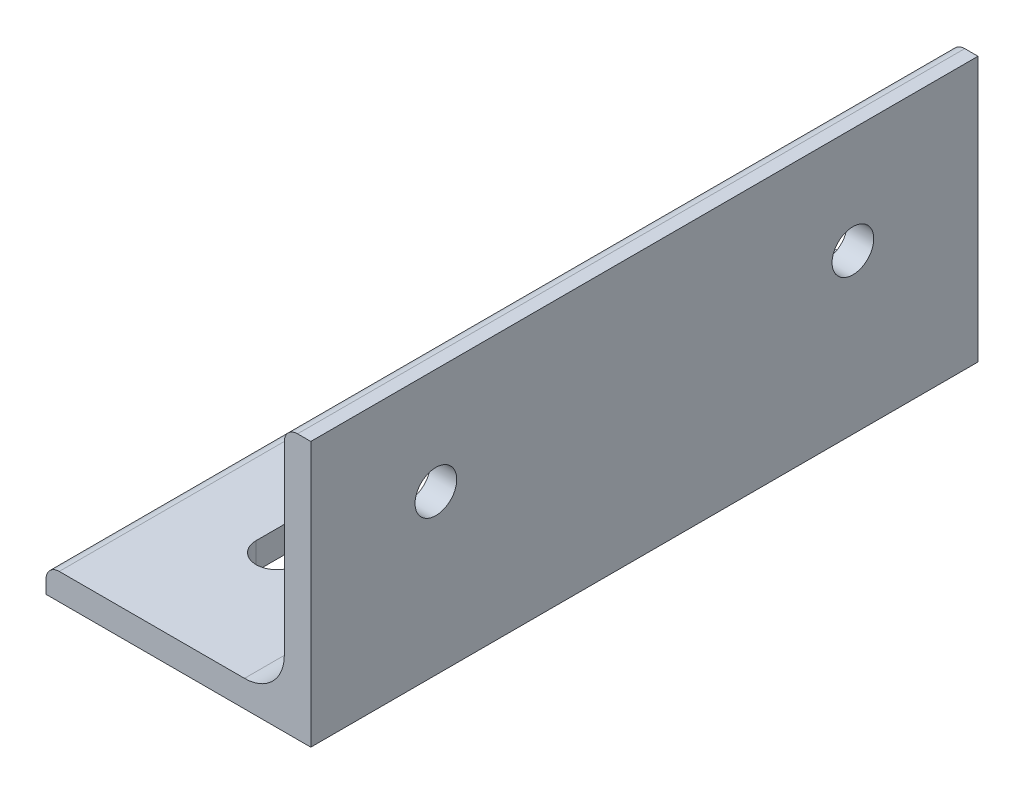
SolidWorks part; units mm, degrees
ref_plane "Front Plane" through (0, 0, 0) normal (0, 0, 1) x (1, 0, 0)
ref_plane "Top Plane" through (0, 0, 0) normal (0, 1, 0) x (1, 0, 0)
ref_plane "Right Plane" through (0, 0, 0) normal (1, 0, 0) x (0, 0, -1)
sketch "Sketch0" plane through (0, 0, 0) normal (0, 0, 1) x (1, 0, 0)
  line L0 (-15.875, -15.875) -> (15.875, -15.875)
  line L1 (15.875, -15.875) -> (15.875, 15.875)
  line L2 (15.875, 0) -> (0, 0) construction
  line L3 (0, 0) -> (0, -15.875) construction
  line L4 (12.7, -7.9248) -> (12.7, 15.875) construction
  line L5 (7.9248, -12.7) -> (-15.875, -12.7) construction
  arc A0 (12.7, -7.9248) -> (7.9248, -12.7) centre (7.9248, -7.9248) cw
  point P3 (11.3014, -11.3014)
  dimension "Inside Corner Radius" = 4.7752
  dimension "Outside Height" = 31.75
  dimension "Inside Height" = 28.575
  dimension "Inside Width" = 28.575
  dimension "Wall Thickness" = 3.175
  dimension "D1" = 3.175
  dimension "Outside Width" = 31.75
sketch "Sketch1" plane through (0, 0, 0) normal (1, 0, 0) x (0, 0, -1)
  line L0 (304.8, 0) -> (-304.8, 0)
  point P4 (0, 0)
  dimension "Length" = 609.6
sketch "Sketch2" plane through (0, 0, 0) normal (0, 0, 1) x (1, 0, 0)
  line L0 (-15.875, -15.875) -> (15.875, -15.875)
  line L1 (15.875, -15.875) -> (15.875, 15.875)
  line L2 (15.875, 15.875) -> (12.7, 15.875) construction
  line L3 (12.7, 14.2875) -> (12.7, -7.9248)
  line L4 (7.9248, -12.7) -> (-14.2875, -12.7)
  line L5 (-15.875, -15.875) -> (-15.875, -12.7) construction
  line L6 (14.2875, 15.875) -> (15.875, 15.875)
  line L7 (-15.875, -14.2875) -> (-15.875, -15.875)
  line L8 (15.875, 0) -> (0, 0) construction
  line L9 (0, 0) -> (0, -15.875) construction
  arc A0 (12.7, 14.2875) -> (14.2875, 15.875) centre (14.2875, 14.2875) cw
  arc A1 (-15.875, -14.2875) -> (-14.2875, -12.7) centre (-14.2875, -14.2875) cw
  arc A2 (12.7, -7.9248) -> (7.9248, -12.7) centre (7.9248, -7.9248) cw
  dimension "Inside Radius" = 4.7752
  dimension "Height" = 31.75
  dimension "Width" = 31.75
  dimension "Thickness" = 3.175
extrude "Boss-Extrude1" add sketch "Sketch2" along normal mid plane 609.6
sketch "Break Locations" plane through (0, 0, 0) normal (1, 0, 0) x (0, 0, -1)
  line L0 (-272.415, 0) -> (272.415, 0)
  line L1 (-304.8, -15.875) -> (-304.8, 15.875) construction
  line L2 (304.8, -15.875) -> (304.8, 15.875) construction
  point P0 (-277.8125, 0)
  point P1 (277.8125, 0)
  point P10 (0, 0)
  point P11 (272.415, 0)
  point P13 (-272.415, 0)
  dimension "D1" = 26.9875
  dimension "D2" = 26.9875
  dimension "D3" = 32.385
sketch "Sketch3" plane through (0, 0, -304.8) normal (0, 0, -1) x (-1, 0, 0)
  line L1 (-15.875, -15.875) -> (18.5395, -15.875)
  line L2 (-15.875, -15.875) -> (-15.875, 17.7829)
  line L3 (-15.875, 17.7829) -> (18.5395, 17.7829)
  line L4 (18.5395, -15.875) -> (18.5395, 17.7829)
extrude "Cut-Extrude1" cut sketch "Sketch3" against normal offset from surface (529.6 mm away) 80 up to face at (3.7396, -3.7396, 304.8)
sketch "Sketch4" plane through (0, -12.7, 0) normal (0, 1, 0) x (1, 0, 0)
  line L0 (-14.2875, -224.8) -> (7.9248, -224.8) construction
  line L1 (7.9248, -304.8) -> (-14.2875, -304.8) construction
  line L2 (-0.6813, -239.8) -> (-0.6813, -289.8)
  line L3 (-5.6814, -239.8) -> (-5.6813, -289.8)
  arc A0 (-0.6813, -239.8) -> (-5.6814, -239.8) centre (-3.1813, -239.8) ccw
  arc A1 (-5.6813, -289.8) -> (-0.6813, -289.8) centre (-3.1813, -289.8) ccw
  point P5 (-3.1813, -224.8)
  dimension "D1" = 5
  dimension "D2" = 5
  dimension "D3" = 15
  dimension "D4" = 15
sketch "Sketch5" plane through (12.7, 0, 0) normal (-1, 0, 0) x (0, 0, 1)
  line L0 (224.8, -7.9248) -> (224.8, 14.2875) construction
  line L1 (304.8, 14.2875) -> (304.8, -7.9248) construction
  circle A2 centre (289.8, 3.1813) radius 2.5
  circle A3 centre (239.8, 3.1813) radius 2.5
  point P3 (224.8, 3.1813)
  dimension "D1" = 5
  dimension "D2" = 5
  dimension "D3" = 15
  dimension "D4" = 15
extrude "Cut-Extrude2" cut sketch "Sketch5" against normal blind 101.6
extrude "Cut-Extrude3" cut sketch "Sketch4" against normal blind 101.6
equation "\"D1@Break Locations\" = .85 * \"Height@Sketch2\""
equation "\"D2@Break Locations\"=\"D1@Break Locations\""
equation "\"Thickness@Sketch2\"=\"wall thickness@sketch0\""
equation "\"Height@Sketch2\"=\"outside height@sketch0\""
equation "\"Width@Sketch2\"=\"outside width@sketch0\""
equation "\"Inside Radius@Sketch2\"=\"inside corner radius@sketch0\""
equation "\"Length@Boss-Extrude1\"=\"length@sketch1\""
equation "\"D3@Break Locations\"=\"D2@Break Locations\"*1.2"
equation "\"D1@Sketch0\"=\"Wall Thickness@Sketch0\""
equation "\"D2@Sketch4\"=\"D1@Sketch4\""
